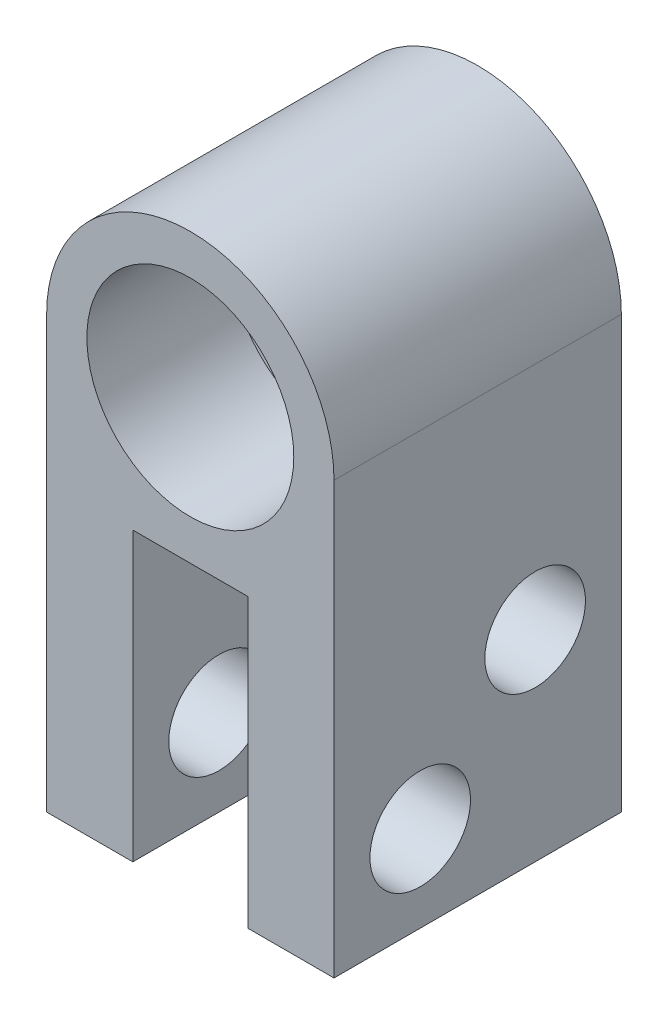
SolidWorks part; units mm, degrees
ref_plane "Plano frontal" through (0, 0, 0) normal (0, 0, 1) x (1, 0, 0)
ref_plane "Plano superior" through (0, 0, 0) normal (0, 1, 0) x (1, 0, 0)
ref_plane "Plano direito" through (0, 0, 0) normal (1, 0, 0) x (0, 0, -1)
sketch "Esboço1" plane through (0, 0, 0) normal (0, 0, 1) x (1, 0, 0)
  circle A0 centre (0, 0) radius 5
  circle A1 centre (0, 0) radius 1.75
  dimension "D1" = 10
  dimension "D2" = 3.5
extrude "Ressalto-extrusão1" add sketch "Esboço1" along normal blind 10
sketch "Esboço2" plane through (0, 0, 10) normal (0, 0, 1) x (1, 0, 0)
  circle A0 centre (0, 0) radius 3.6
  dimension "D1" = 7.2
extrude "Corte-extrusão1" cut sketch "Esboço2" against normal blind 5
sketch "Esboço3" plane through (0, 0, 10) normal (0, 0, 1) x (1, 0, 0)
  line L0 (2, -5) -> (-2, -5) construction
  line L1 (-2, -4.5826) -> (2, -4.5826)
  line L2 (-2, -4.5826) -> (-2, -15)
  line L3 (-2, -15) -> (2, -15)
  line L4 (2, -4.5826) -> (2, -15)
  line L6 (-2, -15) -> (-5, -15)
  line L7 (-2, -15) -> (-2, 0)
  line L8 (-2, 0) -> (-5, 0)
  line L9 (-5, -15) -> (-5, 0)
  line L10 (2, -15) -> (5, -15)
  line L11 (2, -15) -> (2, 0)
  line L12 (2, 0) -> (5, 0)
  line L13 (5, -15) -> (5, 0)
  circle A0 centre (0, 0) radius 5 construction
  point P4 (0, -4.5826)
  circle M11 centre (0, 0) radius 5
  dimension "D1" = 4
  dimension "D2" = 10
  dimension "D3" = 3
extrude "Ressalto-extrusão2" add sketch "Esboço3" against normal blind 10 contours L10 L13 L4 L11 M11 | L9 L6 L7 L2 M11 | L0 L2 M11 | L0 L4 M11 | L1 M11
sketch "Esboço4" plane through (-5, 0, 0) normal (-1, 0, 0) x (0, 0, 1)
  line L0 (0, -15) -> (10, -15) construction
  line L1 (10, -15) -> (10, 0) construction
  line L2 (0, -15) -> (0, 0) construction
  circle A0 centre (7, -12) radius 1.75
  circle A1 centre (3, -8) radius 1.75
  dimension "D1" = 3.5
  dimension "D2" = 3.5
  dimension "D3" = 3
  dimension "D4" = 7
  dimension "D5" = 3
  dimension "D6" = 3
extrude "Corte-extrusão2" cut sketch "Esboço4" against normal blind 10
